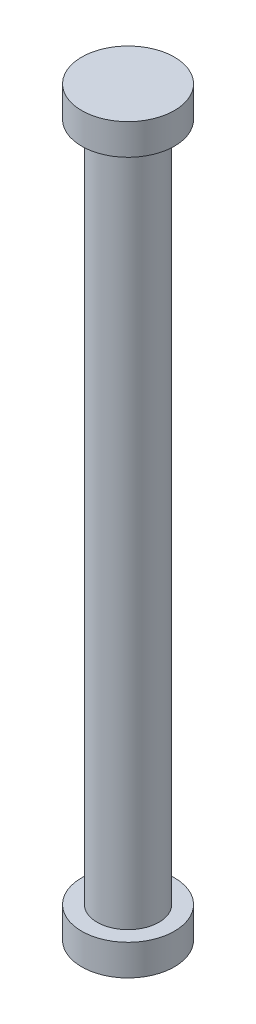
SolidWorks part; units mm, degrees
ref_plane "Front Plane" through (0, 0, 0) normal (0, 0, 1) x (1, 0, 0)
ref_plane "Top Plane" through (0, 0, 0) normal (0, 1, 0) x (1, 0, 0)
ref_plane "Right Plane" through (0, 0, 0) normal (1, 0, 0) x (0, 0, -1)
sketch "Sketch1" plane through (0, 0, 0) normal (0, 1, 0) x (1, 0, 0)
  circle A0 centre (0, 0) radius 1
  dimension "D1" = 2
extrude "Boss-Extrude1" add sketch "Sketch1" along normal blind 22
sketch "Sketch2" plane through (0, 0, 0) normal (0, -1, 0) x (1, 0, 0)
  circle A0 centre (0, 0) radius 1.5
  dimension "D1" = 3
extrude "Boss-Extrude2" add sketch "Sketch2" along normal blind 1
ref_plane "Plane1" through (0, 11, 0) normal (0, 1, 0) x (1, 0, 0)
mirror "Mirror2" about plane through (0, 11, 0) normal (0, 1, 0) of "Boss-Extrude2"
